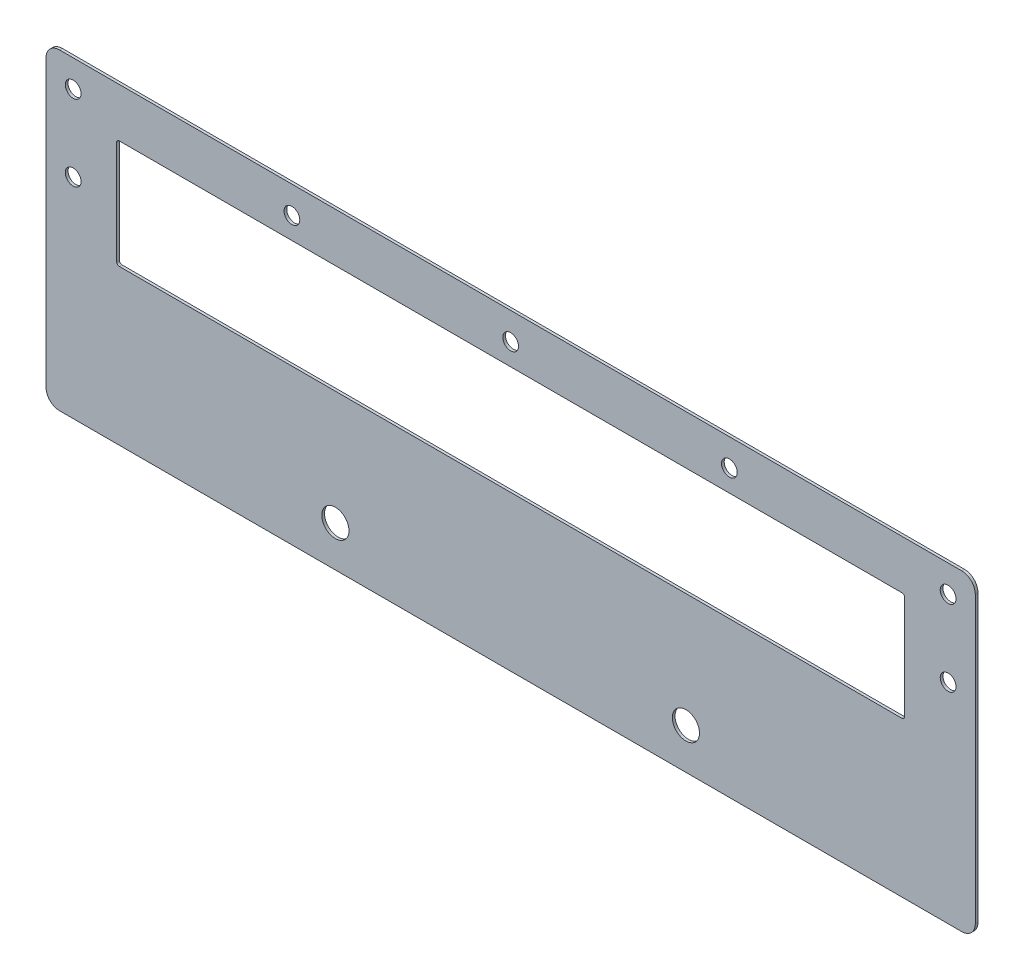
SolidWorks part; units mm, degrees
ref_plane "Front Plane" through (0, 0, 0) normal (0, 0, 1) x (1, 0, 0)
ref_plane "Top Plane" through (0, 0, 0) normal (0, 1, 0) x (1, 0, 0)
ref_plane "Right Plane" through (0, 0, 0) normal (1, 0, 0) x (0, 0, -1)
sketch "Sketch1" plane through (0, 0, 0) normal (0, 0, 1) x (1, 0, 0)
  line L1 (171, -57.5) -> (-171, -57.5)
  line L2 (171, -57.5) -> (171, 57.5)
  line L3 (171, 57.5) -> (-171, 57.5)
  line L4 (-171, -57.5) -> (-171, 57.5)
  line L5 (171, -57.5) -> (-171, 57.5) construction
  line L6 (171, 57.5) -> (-171, -57.5) construction
  line L7 (143, 3.5) -> (-143, 3.5) construction
  line L8 (143, 3.5) -> (143, 37.5) construction
  line L9 (143, 37.5) -> (-143, 37.5) construction
  line L10 (-143, 3.5) -> (-143, 37.5) construction
  line L11 (143, 3.5) -> (-143, 37.5) construction
  line L12 (143, 37.5) -> (-143, 3.5) construction
  line L14 (-143, 36.5) -> (-143, 2.5) construction
  line L15 (142, 37.5) -> (-142, 37.5) construction
  line L16 (143, 2.5) -> (143, 36.5) construction
  line L18 (-145, -0.5) -> (-145, 39.5)
  line L19 (145, 39.5) -> (-145, 39.5)
  line L20 (145, -0.5) -> (145, 39.5)
  line L21 (145, -0.5) -> (-145, -0.5)
  line L22 (-142, 1.5) -> (142, 1.5) construction
  line L23 (-143, 36.5) -> (-143, 2.5) construction
  line L24 (142, 37.5) -> (-142, 37.5) construction
  line L25 (143, 2.5) -> (143, 36.5) construction
  point P0 (0, 0)
  point P6 (0, 20.5)
  dimension "D1" = 342
  dimension "D2" = 115
  dimension "D3" = 2
  dimension "D4" = 2
  dimension "D5" = 2
  dimension "D6" = 2
extrude "Boss-Extrude1" add sketch "Sketch1" along normal blind 1
fillet "Fillet1" radius 5 4 edges at (-171, 57.5, 0.5) (171, -57.5, 0.5) (-171, -57.5, 0.5) (171, 57.5, 0.5)
fillet "Fillet2" radius 1 4 edges at (145, 39.5, 0.5) (-145, -0.5, 0.5) (145, -0.5, 0.5) (-145, 39.5, 0.5)
hole_wizard "M5 Clearance Hole1" positions "Sketch2" profile "Sketch3" hole size "M5" standard "ISO" end condition through all
sketch "Sketch2" plane through (0, 0, 1) normal (0, 0, 1) x (1, 0, 0)
  point P0 (-161, 47.5)
  point P3 (-161, 19.5)
  point P6 (-80.5, 47.5)
  point P9 (0, 47.5)
  point P12 (80.5, 47.5)
  point P15 (161, 47.5)
  point P18 (161, 19.5)
sketch "Sketch3" plane through (-161, 47.5, 1) normal (1, 0, 0) x (0, -1, 0)
  line L0 (0, 0) -> (0, 1)
  line L1 (0, 1) -> (2.9, 1)
  line L2 (2.9, 1) -> (2.9, 0)
  line L5 (2.9, 0) -> (0, 0)
  line L11 (0, -6.35) -> (0, 107.95) construction
  dimension "Thru Hole Dia." = 5.8
  dimension "Thru Hole Depth" = 1
hole_wizard "M8 Clearance Hole1" positions "Sketch4" profile "Sketch5" hole size "M8" standard "ISO" end condition through all
sketch "Sketch4" plane through (0, 0, 1) normal (0, 0, 1) x (1, 0, 0)
  point P0 (-64.5, -42.5)
  point P3 (64.5, -42.5)
sketch "Sketch5" plane through (-64.5, -42.5, 1) normal (1, 0, 0) x (0, -1, 0)
  line L0 (0, 0) -> (0, 1)
  line L1 (0, 1) -> (5, 1)
  line L2 (5, 1) -> (5, 0)
  line L5 (5, 0) -> (0, 0)
  line L11 (0, -6.35) -> (0, 107.95) construction
  dimension "Thru Hole Dia." = 10
  dimension "Thru Hole Depth" = 1
